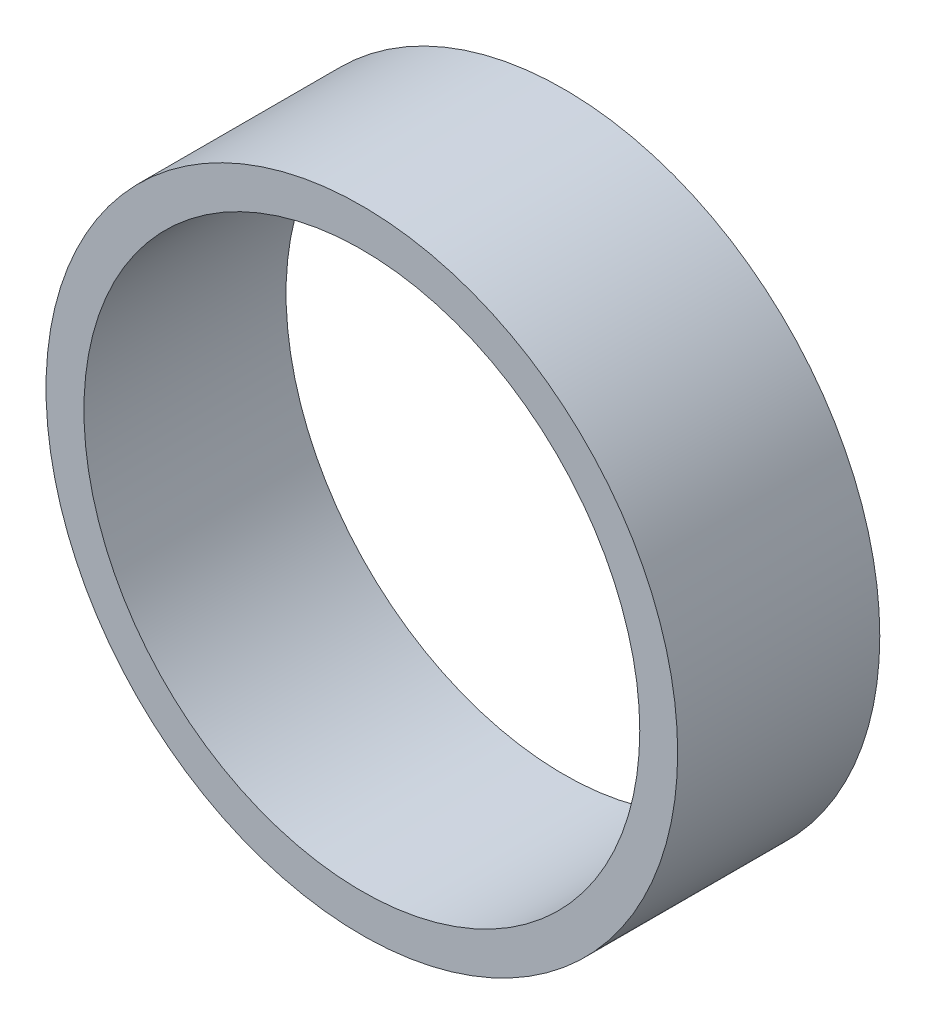
SolidWorks part; units mm, degrees
material "POLYURETHANE (11671)"
ref_plane "Front Plane" through (0, 0, 0) normal (0, 0, 1) x (1, 0, 0)
ref_plane "Top Plane" through (0, 0, 0) normal (0, 1, 0) x (1, 0, 0)
ref_plane "Right Plane" through (0, 0, 0) normal (1, 0, 0) x (0, 0, -1)
sketch "Sketch2" plane through (0, 0, 0) normal (0, 0, 1) x (1, 0, 0)
  circle A0 centre (0, 0) radius 55
  circle A1 centre (0, 0) radius 62.5
  dimension "D1" = 110
  dimension "D2" = 125
extrude "Boss-Extrude1" add sketch "Sketch2" along normal mid plane 40
